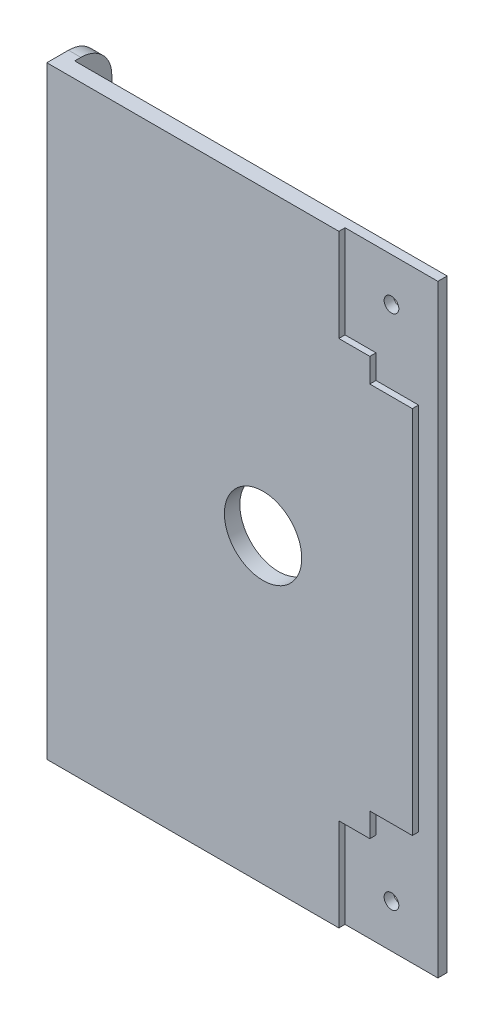
SolidWorks part; units mm, degrees
ref_plane "Alzado" through (0, 0, 0) normal (0, 0, 1) x (1, 0, 0)
ref_plane "Planta" through (0, 0, 0) normal (0, 1, 0) x (1, 0, 0)
ref_plane "Vista lateral" through (0, 0, 0) normal (1, 0, 0) x (0, 0, -1)
sketch "Croquis1" plane through (0, 0, 0) normal (0, 0, 1) x (1, 0, 0)
  line L1 (-117.2917, 97.7627) -> (131.4683, 97.7627)
  line L2 (-117.2917, 97.7627) -> (-117.2917, -97.2373)
  line L3 (-117.2917, -97.2373) -> (131.4683, -97.2373)
  line L4 (131.4683, 97.7627) -> (131.4683, -97.2373)
  dimension "D1" = 248.76
  dimension "D2" = 195
extrude "Saliente-Extruir1" add sketch "Croquis1" along normal blind 5
sketch "Croquis2" plane through (0, 0, 5) normal (0, 0, 1) x (1, 0, 0)
  line L0 (-117.2917, 0.2627) -> (131.4683, 0.2627) construction
  line L1 (-117.2917, 97.7627) -> (-117.2917, -97.2373) construction
  line L2 (131.4683, -97.2373) -> (131.4683, 97.7627) construction
  line L3 (-117.2917, -97.2373) -> (-69.2917, -97.2373)
  line L4 (-117.2917, -97.2373) -> (131.4683, -97.2373) construction
  line L5 (-69.2917, -97.2373) -> (-69.2917, -67.2373)
  line L6 (-69.2917, -67.2373) -> (-117.2917, -67.2373)
  line L7 (-117.2917, -67.2373) -> (-117.2917, -97.2373)
  line L8 (131.4683, 67.7627) -> (101.4683, 67.7627)
  line L9 (131.4683, -97.2373) -> (101.4683, -97.2373)
  line L10 (131.4683, -97.2373) -> (131.4683, -67.2373)
  line L11 (131.4683, -67.2373) -> (101.4683, -67.2373)
  line L12 (101.4683, -97.2373) -> (101.4683, -67.2373)
  line L13 (101.4683, 97.7627) -> (101.4683, 67.7627)
  line L14 (131.4683, 97.7627) -> (101.4683, 97.7627)
  line L15 (131.4683, 97.7627) -> (131.4683, 67.7627)
  line L16 (-69.2917, 67.7627) -> (-117.2917, 67.7627)
  line L17 (-69.2917, 97.7627) -> (-69.2917, 67.7627)
  line L18 (-117.2917, 97.7627) -> (-69.2917, 97.7627)
  line L19 (-117.2917, 67.7627) -> (-117.2917, 97.7627)
  dimension "D1" = 48
  dimension "D2" = 30
  dimension "D3" = 30
  dimension "D4" = 30
extrude "Cortar-Extruir1" cut sketch "Croquis2" against normal blind 2
sketch "Croquis3" plane through (0, 0, 5) normal (0, 0, 1) x (1, 0, 0)
  line L0 (-69.2917, 97.7627) -> (-117.2917, 97.7627) construction
  line L1 (116.4683, 83.7627) -> (116.4683, 67.7627) construction
  line L3 (116.4683, -83.2373) -> (116.4683, -67.2373) construction
  line L5 (131.4683, -67.2373) -> (101.4683, -67.2373) construction
  line L6 (101.4683, 67.7627) -> (131.4683, 67.7627) construction
  line L7 (-93.2917, 83.7627) -> (-93.2917, 67.7627) construction
  line L8 (-117.2917, 67.7627) -> (-69.2917, 67.7627) construction
  line L9 (-93.2917, -83.2373) -> (-93.2917, -67.2373) construction
  line L10 (-69.2917, -67.2373) -> (-117.2917, -67.2373) construction
  circle A0 centre (-93.2917, 83.7627) radius 2.375
  circle A1 centre (-93.2917, -83.2373) radius 2.375
  circle A2 centre (116.4683, 83.7627) radius 2.375
  circle A3 centre (116.4683, -83.2373) radius 2.375
  dimension "D2" = 4.75
  dimension "D3" = 4.75
  dimension "D5" = 4.75
  dimension "D6" = 4.75
  dimension "D1" = 14
  dimension "D4" = 14
  dimension "D7" = 209.76
  dimension "D8" = 16
  dimension "D9" = 16
extrude "Cortar-Extruir2" cut sketch "Croquis3" against normal blind 10
sketch "Croquis4" plane through (0, 0, 0) normal (0, 0, -1) x (-1, 0, 0)
  line L7 (-131.4683, 97.7627) -> (117.2917, 97.7627) construction
  line L9 (117.2917, 97.7627) -> (117.2917, -97.2373) construction
  circle A0 centre (55.1017, 0.2627) radius 40
  dimension "D3" = 80
  dimension "D1" = 62.19
  dimension "D2" = 97.5
extrude "Saliente-Extruir2" add sketch "Croquis4" along normal blind 206 contours A0
sketch "Croquis5" plane through (0, 0, 0) normal (0, 0, -1) x (-1, 0, 0)
  line L0 (-131.4683, 0.2627) -> (117.2917, 0.2627) construction
  line L1 (-131.4683, -97.2373) -> (-131.4683, 97.7627) construction
  line L2 (117.2917, 97.7627) -> (117.2917, -97.2373) construction
  circle A0 centre (-76.9683, 0.2627) radius 12.5
  dimension "D1" = 25
  dimension "D2" = 54.5
extrude "Cortar-Extruir3" cut sketch "Croquis5" against normal blind 10
sketch "Croquis6" plane through (0, 0, 0) normal (0, 0, -1) x (-1, 0, 0)
  line L0 (-131.4683, 97.7627) -> (117.2917, 97.7627) construction
  line L1 (-7.0883, 97.7627) -> (-7.0883, -97.2373)
  line L2 (117.2917, -97.2373) -> (-131.4683, -97.2373) construction
  line L3 (-7.0883, 97.7627) -> (117.2917, 97.7627)
  line L4 (117.2917, 97.7627) -> (117.2917, -97.2373)
  line L5 (117.2917, -97.2373) -> (-7.0883, -97.2373)
  line L6 (-131.4683, 0.2627) -> (56.0317, 0.2627)
  line L7 (-131.4683, -97.2373) -> (-131.4683, 97.7627) construction
  circle A1 centre (56.0317, 0.2627) radius 100
  dimension "D1" = 200
  dimension "D2" = 187.5
sketch "Croquis9" plane through (0, 97.7627, 0) normal (0, 1, 0) x (1, 0, 0)
  line L0 (7.0883, 0) -> (7.0883, -5)
  line L1 (131.4683, 0) -> (-117.2917, 0) construction
  line L2 (101.4683, -5) -> (-69.2917, -5) construction
ref_plane "Plano3" through (7.0883, 0, 0) normal (1, 0, 0) x (0, 0, -1)
sketch "Croquis12" plane through (7.0883, 0, 0) normal (1, 0, 0) x (0, 0, -1)
  line L0 (0, 97.7627) -> (0, 67.7627)
  line L1 (0, 67.7627) -> (12, 67.7627)
  line L2 (12, 67.7627) -> (12, 97.7627)
  line L3 (12, 97.7627) -> (0, 97.7627)
  line L4 (0, -97.2373) -> (12, -97.2373)
  line L5 (12, -97.2373) -> (12, -67.2373)
  line L6 (12, -67.2373) -> (0, -67.2373)
  line L7 (0, -67.2373) -> (0, -97.2373)
  dimension "D1" = 30
  dimension "D2" = 12
  dimension "D3" = 30
  dimension "D4" = 12
extrude "Saliente-Extruir3" add sketch "Croquis12" along normal mid plane 8
fillet "Redondeo1" radius 10 2 edges at (7.0883, -67.2373, 0) (7.0883, 67.7627, 0)
fillet "Redondeo2" radius 10 2 edges at (7.0883, 67.7627, -12) (7.0883, -67.2373, -12)
fillet "Redondeo3" radius 10 2 edges at (7.0883, -97.2373, -12) (7.0883, 97.7627, -12)
sketch "Croquis13" plane through (11.0883, 0, 0) normal (1, 0, 0) x (0, 0, -1)
  line L0 (-5, 0.2627) -> (206, 0.2627) construction
  line L1 (-5, -67.2373) -> (-5, 67.7627) construction
  line L2 (206, -39.7373) -> (206, 40.2627) construction
  line L3 (6, 87.7627) -> (12, 87.7627) construction
  line L4 (6, 87.7627) -> (6, 77.7627) construction
  circle A0 centre (6, 87.7627) radius 1.625
  circle A1 centre (6, 77.7627) radius 1.625
  circle A2 centre (6, -77.2373) radius 1.625
  circle A3 centre (6, -87.2373) radius 1.625
  dimension "D3" = 3.25
  dimension "D4" = 3.25
  dimension "D1" = 6
extrude "Cortar-Extruir5" cut sketch "Croquis13" against normal through all both and the other way through all
sketch "Croquis14" plane through (0, 0, 0) normal (0, 0, -1) x (-1, 0, 0)
  line L0 (-7.0883, 97.7627) -> (-7.0883, -97.2373)
  line L1 (-7.0883, 97.7627) -> (117.2917, 97.7627)
  line L2 (117.2917, 97.7627) -> (117.2917, -97.2373)
  line L3 (117.2917, -97.2373) -> (-7.0883, -97.2373)
sketch "Croquis15" plane through (0, 0, 5) normal (0, 0, 1) x (1, 0, 0)
  line L0 (111.4683, 67.7627) -> (131.4683, 67.7627)
  line L1 (111.4683, 67.7627) -> (111.4683, 60.0127)
  line L2 (131.4683, -67.2373) -> (101.4683, -67.2373) construction
  line L3 (111.4683, -67.2373) -> (111.4683, -59.4873)
  line L4 (111.4683, -59.4873) -> (125.2183, -59.4873)
  line L5 (125.2183, -59.4873) -> (125.2183, 60.0127)
  line L6 (111.4683, 60.0127) -> (125.2183, 60.0127)
  line L7 (111.4683, -67.2373) -> (131.4683, -67.2373)
  line L10 (131.4683, -67.2373) -> (131.4683, 67.7627)
  dimension "D1" = 119.5
  dimension "D2" = 7.75
  dimension "D3" = 13.75
extrude "Cortar-Extruir7" cut sketch "Croquis15" against normal blind 2
sketch "Croquis16" plane through (0, 0, 5) normal (0, 0, 1) x (1, 0, 0)
  circle A1 centre (-55.1017, 20.2627) radius 1.75
  circle A2 centre (-35.1017, 0.2627) radius 1.75
  circle A3 centre (-55.1017, -19.7373) radius 1.75
  circle A4 centre (-75.1017, 0.2627) radius 1.75
  dimension "D3" = 3.5
  dimension "D4" = 4
extrude "Cortar-Extruir9" cut sketch "Croquis16" against normal blind 20
extrude "Cortar-Extruir16" cut sketch "Croquis14" against normal through all both and the other way through all
